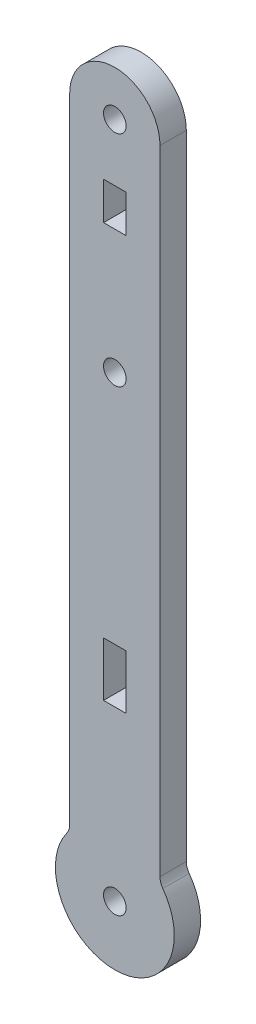
SolidWorks part; units mm, degrees
material "Balsa"
ref_plane "Front Plane" through (0, 0, 0) normal (0, 0, 1) x (1, 0, 0)
ref_plane "Top Plane" through (0, 0, 0) normal (0, 1, 0) x (1, 0, 0)
ref_plane "Right Plane" through (0, 0, 0) normal (1, 0, 0) x (0, 0, -1)
sketch "Sketch1" plane through (0, 0, 0) normal (0, 0, 1) x (1, 0, 0)
  line L0 (0, 0) -> (0, 90) construction
  line L1 (-6, 90) -> (-6, 5.1391)
  line L2 (6, 90) -> (6, 5.1391)
  line L3 (-1.5, 62.377) -> (1.5, 59.377) construction
  line L4 (1.5, 62.377) -> (-1.5, 59.377) construction
  line L11 (-1.5, 29.577) -> (-1.5, 22.377)
  line L12 (1.5, 29.577) -> (-1.5, 29.577)
  line L13 (1.5, 22.377) -> (1.5, 29.577)
  line L14 (-1.5, 22.377) -> (1.5, 22.377)
  line L19 (-1.5, 82.377) -> (-1.5, 77.377)
  line L20 (1.5, 82.377) -> (-1.5, 82.377)
  line L21 (1.5, 77.377) -> (1.5, 82.377)
  line L22 (-1.5, 77.377) -> (1.5, 77.377)
  line L27 (-1.5, 62.377) -> (-1.5, 59.377) construction
  line L28 (1.5, 62.377) -> (-1.5, 62.377) construction
  line L29 (1.5, 59.377) -> (1.5, 62.377) construction
  line L30 (-1.5, 59.377) -> (1.5, 59.377) construction
  circle A0 centre (0, 0) radius 1.5
  arc A2 (-6, 5.1391) -> (6, 5.1391) centre (0, 0) ccw
  arc A3 (-6, 90) -> (6, 90) centre (0, 90) cw
  circle A4 centre (0, 60.877) radius 1.5
  circle A5 centre (0, 90) radius 1.5
  point P24 (0, 22.377)
  dimension "D3" = 15.8
  dimension "D4" = 6
  dimension "D7" = 3
  dimension "D1" = 90
  dimension "D8" = 7.623
  dimension "D9" = 5
  dimension "D10" = 3
  dimension "D11" = 3
  dimension "D12" = 7.2
  dimension "D13" = 22.377
extrude "Boss-Extrude1" add sketch "Sketch1" along normal blind 3.5
fillet "Fillet1" radius 2 2 edges at (-6, 5.1391, 1.75) (6, 5.1391, 1.75)
